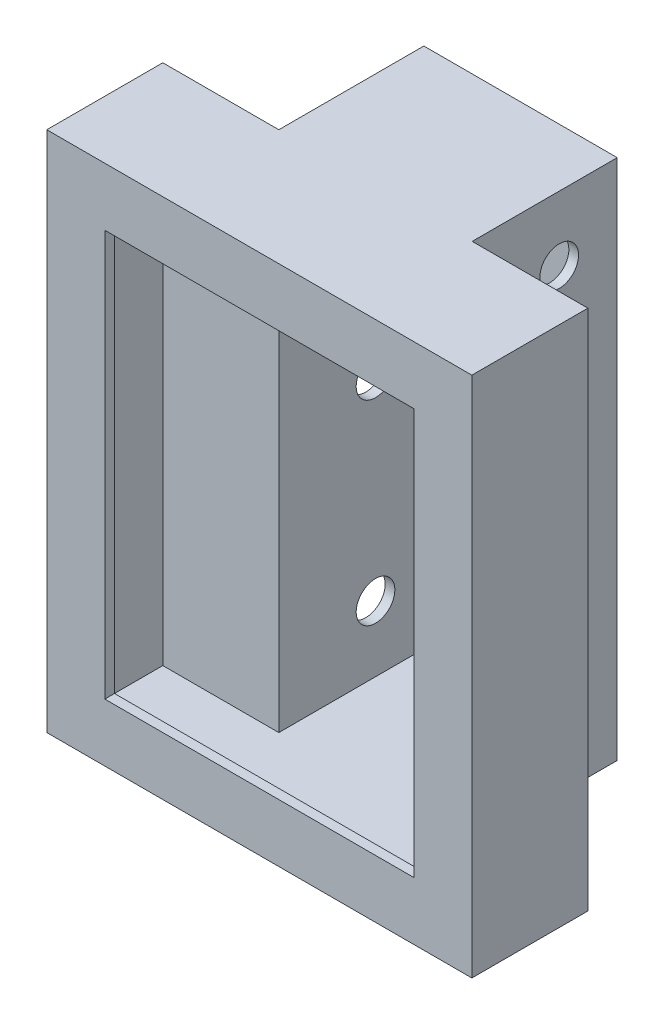
SolidWorks part; units mm, degrees
ref_plane "Plan de face" through (0, 0, 0) normal (0, 0, 1) x (1, 0, 0)
ref_plane "Plan de dessus" through (0, 0, 0) normal (0, 1, 0) x (1, 0, 0)
ref_plane "Plan de droite" through (0, 0, 0) normal (1, 0, 0) x (0, 0, -1)
sketch "Esquisse1" plane through (0, 0, 0) normal (0, 0, 1) x (1, 0, 0)
  line L1 (0, 0) -> (-100, 0)
  line L2 (0, 0) -> (0, 270)
  line L3 (0, 270) -> (-100, 270)
  line L4 (-100, 0) -> (-100, 270)
  dimension "D1" = 100
  dimension "D2" = 270
extrude "Boss.-Extru.1" add sketch "Esquisse1" along normal blind 5
sketch "Esquisse2" plane through (0, 0, 5) normal (0, 0, 1) x (1, 0, 0)
  line L0 (-95, 265) -> (-95, 5)
  line L1 (-100, 270) -> (0, 270)
  line L2 (-100, 270) -> (-100, 0)
  line L3 (-100, 0) -> (0, 0)
  line L4 (0, 270) -> (0, 0)
  line L5 (-95, 5) -> (-5, 5)
  line L6 (-5, 265) -> (-5, 5)
  line L7 (-95, 265) -> (-5, 265)
  dimension "D1" = 5
extrude "Boss.-Extru.2" add sketch "Esquisse2" along normal blind 70
sketch "Esquisse3" plane through (0, 0, 75) normal (0, 0, 1) x (1, 0, 0)
  line L1 (-95, 270) -> (-160, 270)
  line L2 (-95, 270) -> (-95, 0)
  line L3 (-95, 0) -> (-160, 0)
  line L4 (-160, 270) -> (-160, 0)
  line L5 (-5.1681, 270) -> (-5.1681, 0)
  line L6 (-5.1681, 270) -> (59.8319, 270)
  line L8 (-5.1681, 0) -> (59.8319, 0)
  line L9 (59.8319, 270) -> (59.8319, 0)
  dimension "D1" = 65
  dimension "D2" = 65
extrude "Boss.-Extru.4" add sketch "Esquisse3" along normal blind 5
sketch "Esquisse5" plane through (0, 0, 75) normal (0, 0, 1) x (1, 0, 0)
  line L1 (-95, 270) -> (-5, 270)
  line L2 (-95, 270) -> (-95, 265)
  line L3 (-95, 265) -> (-5, 265)
  line L4 (-5, 270) -> (-5, 265)
  line L5 (-95, 5) -> (-5.1681, 5)
  line L6 (-95, 5) -> (-95, 0)
  line L7 (-95, 0) -> (-5.1681, 0)
  line L8 (-5.1681, 5) -> (-5.1681, 0)
extrude "Boss.-Extru.5" add sketch "Esquisse5" along normal blind 5
sketch "Esquisse6" plane through (0, 0, 80) normal (0, 0, 1) x (1, 0, 0)
  line L0 (-155, 265) -> (-155, 5)
  line L1 (-160, 270) -> (59.8319, 270)
  line L2 (-160, 270) -> (-160, 0)
  line L3 (-160, 0) -> (59.8319, 0)
  line L4 (59.8319, 270) -> (59.8319, 0)
  line L5 (-155, 5) -> (54.8319, 5)
  line L6 (54.8319, 265) -> (54.8319, 5)
  line L7 (-155, 265) -> (54.8319, 265)
  dimension "D1" = 5
extrude "Boss.-Extru.6" add sketch "Esquisse6" along normal blind 50
sketch "Esquisse7" plane through (-100, 0, 0) normal (-1, 0, 0) x (0, 0, 1)
  line L0 (0, 270) -> (0, 0) construction
  line L1 (75, 0) -> (0, 0) construction
  circle A3 centre (30, 140) radius 10
  circle A4 centre (30, 38.976) radius 10
  circle A5 centre (30, 236.4006) radius 10
  dimension "D1" = 30
  dimension "D3" = 20
  dimension "D4" = 20
  dimension "D5" = 20
  dimension "D6" = 30
  dimension "D7" = 30
  dimension "D2" = 140
extrude "Enlèv. mat.-Extru.1" cut sketch "Esquisse7" against normal through all
sketch "Esquisse8" plane through (0, 0, 130) normal (0, 0, 1) x (1, 0, 0)
  line L0 (-160, 0) -> (59.8319, 0) construction
  line L1 (-160, 270) -> (-130, 270)
  line L2 (-160, 270) -> (-160, 0)
  line L3 (-160, 0) -> (-130, 0)
  line L4 (-130, 240) -> (-130, 30)
  line L6 (59.8319, 270) -> (-130, 270)
  line L7 (59.8319, 270) -> (59.8319, 240)
  line L8 (29.8319, 240) -> (-130, 240)
  line L11 (59.8319, 240) -> (59.8319, 0)
  line L12 (59.8319, 0) -> (29.8319, 0)
  line L13 (29.8319, 240) -> (29.8319, 30)
  line L14 (29.8319, 0) -> (-130, 0)
  line L16 (29.8319, 30) -> (-130, 30)
  dimension "D1" = 30
  dimension "D2" = 30
  dimension "D3" = 30
  dimension "D4" = 30
extrude "Boss.-Extru.7" add sketch "Esquisse8" along normal blind 5
